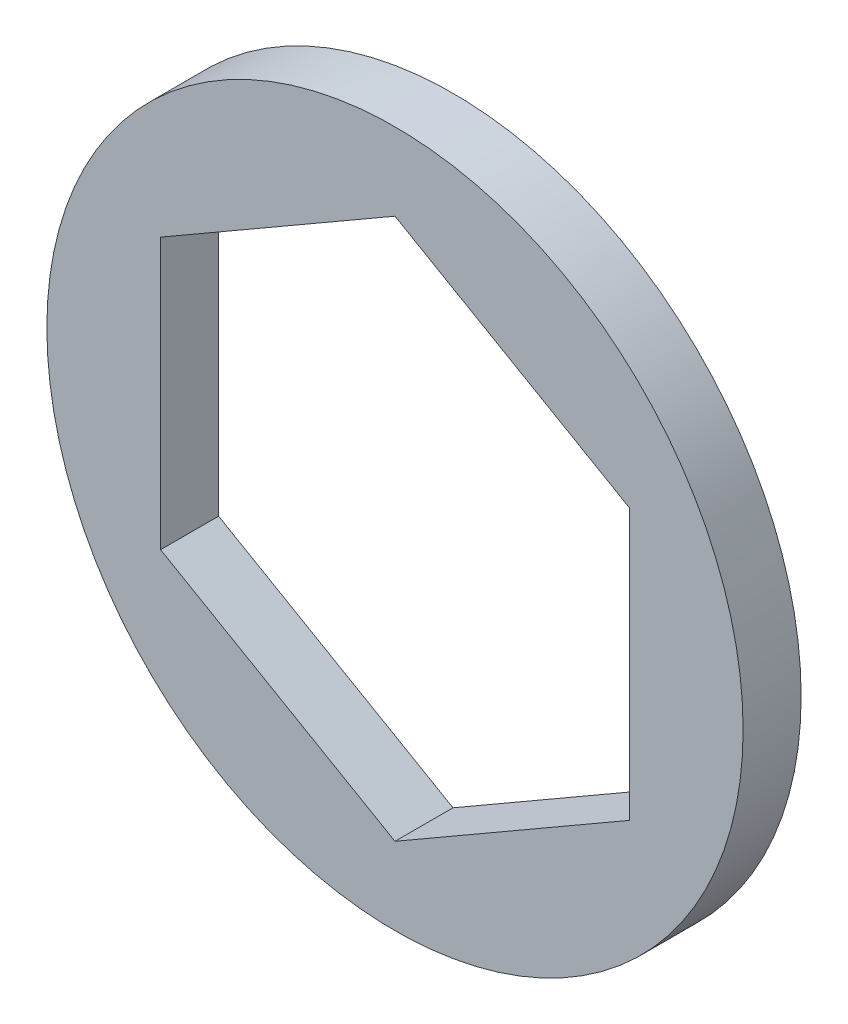
SolidWorks part; units mm, degrees
material "PET"
ref_plane "Front Plane" through (0, 0, 0) normal (0, 0, 1) x (1, 0, 0)
ref_plane "Top Plane" through (0, 0, 0) normal (0, 1, 0) x (1, 0, 0)
ref_plane "Right Plane" through (0, 0, 0) normal (1, 0, 0) x (0, 0, -1)
sketch "Sketch2" plane through (0, 0, 0) normal (0, 0, 1) x (1, 0, 0)
  line L1 (6.4135, 3.7028) -> (0, 7.4057)
  line L2 (0, 7.4057) -> (-6.4135, 3.7028)
  line L3 (-6.4135, 3.7028) -> (-6.4135, -3.7028)
  line L4 (-6.4135, -3.7028) -> (0, -7.4057)
  line L5 (0, -7.4057) -> (6.4135, -3.7028)
  line L6 (6.4135, -3.7028) -> (6.4135, 3.7028)
  circle A0 centre (0, 0) radius 9.525
  circle A1 centre (0, 0) radius 6.4135 construction
  dimension "D1" = 12.827
  dimension "D2" = 19.05
extrude "Boss-Extrude1" add sketch "Sketch2" along normal blind 1.5875
